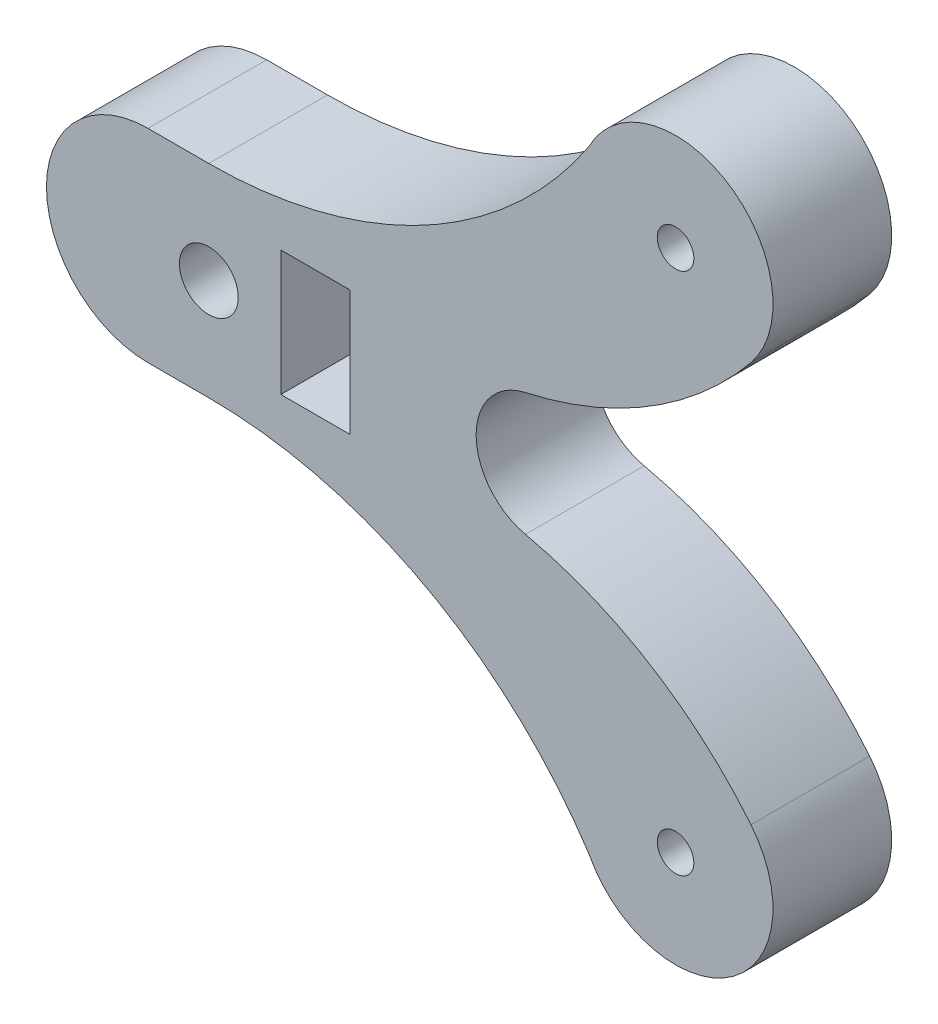
SolidWorks part; units mm, degrees
material "Acrylic (Medium-high impact)"
ref_plane "Front Plane" through (0, 0, 0) normal (0, 0, 1) x (1, 0, 0)
ref_plane "Top Plane" through (0, 0, 0) normal (0, 1, 0) x (1, 0, 0)
ref_plane "Right Plane" through (0, 0, 0) normal (1, 0, 0) x (0, 0, -1)
sketch "Sketch1" plane through (0, 0, 0) normal (0, 0, 1) x (1, 0, 0)
  line L0 (587.4699, 435.3658) -> (583.9197, 435.3658) construction
  line L1 (594.1695, 438.4483) -> (594.1695, 432.2833) construction
  line L2 (592.4695, 438.4483) -> (595.8695, 438.4483)
  line L3 (595.8695, 438.4483) -> (595.8695, 432.2833)
  line L4 (595.8695, 432.2833) -> (592.4695, 432.2833)
  line L5 (592.4695, 432.2833) -> (592.4695, 438.4483)
  line L6 (588.9197, 433.916) -> (588.9197, 430.3658) construction
  line L7 (588.9197, 436.8156) -> (588.9197, 440.3658) construction
  line L8 (592.4695, 435.3658) -> (595.8695, 435.3658) construction
  line L9 (588.9197, 440.3658) -> (585.9197, 440.3658)
  line L10 (611.9197, 448.2658) -> (611.9197, 422.4658) construction
  line L11 (611.9197, 422.4658) -> (611.9197, 427.7978) construction
  line L12 (602.0913, -566.5041) -> (602.0913, 49433.4959) construction
  line L13 (611.9197, 422.4658) -> (611.9197, 417.1338) construction
  line L14 (588.9197, 430.3658) -> (585.9197, 430.3658)
  line L16 (611.9197, 448.2658) -> (611.9197, 453.5978) construction
  line L17 (611.9197, 448.2658) -> (611.9197, 442.9338) construction
  line L20 (607.777, 435.3658) -> (50607.777, 435.3658) construction
  circle A0 centre (611.9197, 448.2658) radius 0.9
  circle A1 centre (611.9197, 422.4658) radius 0.9
  circle A2 centre (588.9197, 435.3658) radius 1.4498
  arc A3 (585.9197, 440.3658) -> (585.9197, 430.3658) centre (585.9197, 435.3658) ccw
  arc A4 (607.6499, 450.4587) -> (615.6343, 445.2258) centre (611.9197, 448.2658) cw
  arc A5 (588.9197, 440.3658) -> (607.6499, 450.4587) centre (588.9197, 462.7918) ccw
  arc A6 (604.5218, 438.3927) -> (604.5218, 432.339) centre (605.1913, 435.3658) ccw
  arc A7 (604.5218, 438.3927) -> (615.6343, 445.2258) centre (600.22, 457.841) ccw
  arc A8 (604.5218, 432.339) -> (615.6343, 425.5059) centre (600.22, 412.8906) cw
  arc A9 (607.6499, 420.2729) -> (615.6343, 425.5059) centre (611.9197, 422.4658) ccw
  arc A10 (588.9197, 430.3658) -> (607.6499, 420.2729) centre (588.9197, 407.9398) cw
  point P33 (602.0913, 435.3658)
  point P35 (590.3695, 435.3658)
  point P37 (611.9197, 453.0658)
  point P39 (611.9197, 417.6658)
  dimension "D1" = 2.1
  dimension "D4" = 1.8
  dimension "D8" = 3.1
  dimension "D10" = 4.8
  dimension "D11" = 3
  dimension "D14" = 35.4
  dimension "D5" = 25.8
  dimension "D2" = 23
  dimension "D3" = 10
  dimension "D6" = 6.165
  dimension "D7" = 3.4
  dimension "D9" = 6.2218
  dimension "D12" = 18.7302
  dimension "D13" = 11.1125
extrude "Boss-Extrude1" add sketch "Sketch1" along normal blind 5.85
